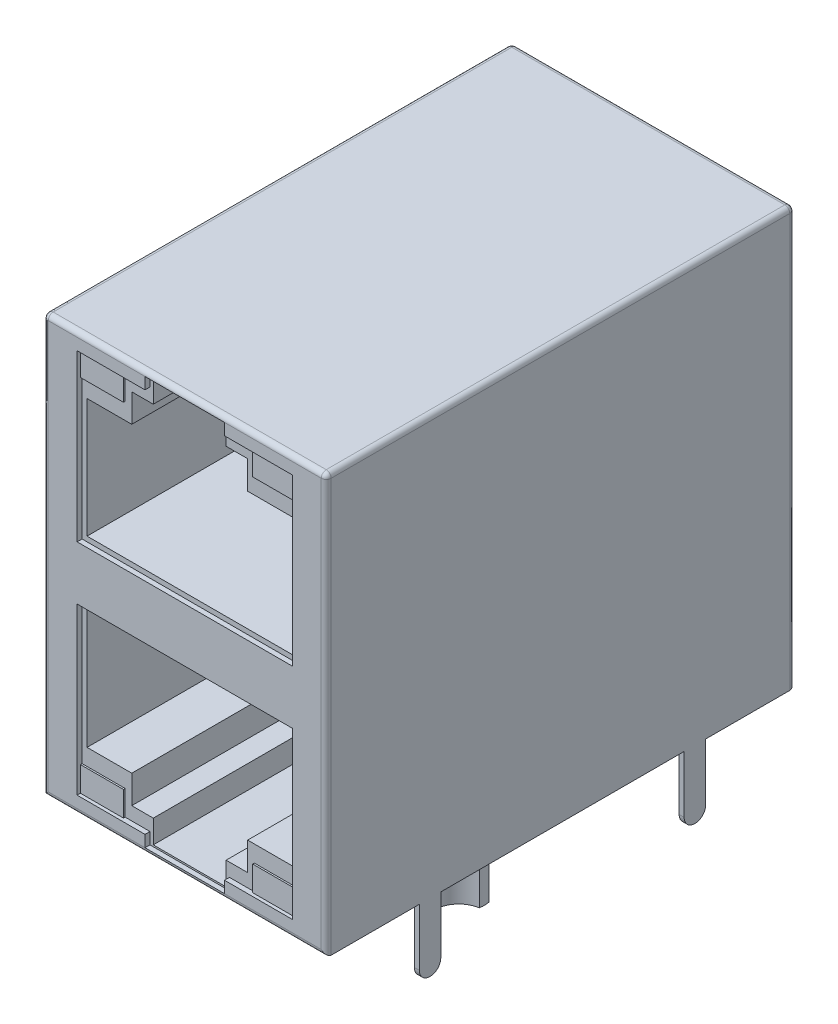
SolidWorks part; units mm, degrees
ref_plane "前视基准面" through (0, 0, 0) normal (0, 0, 1) x (1, 0, 0)
ref_plane "上视基准面" through (0, 0, 0) normal (0, 1, 0) x (1, 0, 0)
ref_plane "右视基准面" through (0, 0, 0) normal (1, 0, 0) x (0, 0, -1)
other "Configuration Table"
sketch "草图1" plane through (0, 0, 0) normal (0, 1, 0) x (1, 0, 0)
  line L0 (0, 0) -> (17.09, 0)
  line L1 (17.09, 0) -> (17.09, 28.3)
  line L2 (17.09, 28.3) -> (0, 28.3)
  line L3 (0, 28.3) -> (0, 0)
extrude "凸台-拉伸1" add sketch "草图1" along normal blind 25.25
sketch "草图2" plane through (17.09, 0, 0) normal (1, 0, 0) x (0, 0, -1)
  line L1 (0, 0) -> (28.3, 0) construction
  line L2 (21.62, 0) -> (21.62, -3.45)
  line L3 (22.92, 0) -> (21.62, 0)
  line L4 (6.92, -3.45) -> (6.92, 0)
  line L5 (6.92, 0) -> (5.62, 0)
  line L6 (5.62, 0) -> (5.62, -3.45)
  line L7 (22.92, -3.45) -> (22.92, 0)
  arc A0 (5.62, -3.45) -> (6.92, -3.45) centre (6.27, -3.45) ccw
  arc A1 (21.62, -3.45) -> (22.92, -3.45) centre (22.27, -3.45) ccw
extrude "凸台-拉伸2" add sketch "草图2" against normal blind 0.3
sketch "草图4" plane through (0, 0, 0) normal (-1, 0, 0) x (0, 0, 1)
  line L3 (-5.62, -3.45) -> (-5.62, 0) construction
  line L4 (-5.62, 0) -> (-6.92, 0) construction
  line L5 (-6.92, 0) -> (-6.92, -3.45) construction
  line L9 (-5.62, -3.45) -> (-5.62, 0)
  line L10 (-5.62, 0) -> (-6.92, 0)
  line L11 (-6.92, 0) -> (-6.92, -3.45)
  line L14 (-25.68, -3.45) -> (-25.68, 0)
  line L15 (-26.98, 0) -> (-26.98, -3.45)
  line L16 (-25.68, 0) -> (-26.98, 0)
  arc A1 (-6.92, -3.45) -> (-5.62, -3.45) centre (-6.27, -3.45) ccw construction
  arc A3 (-6.92, -3.45) -> (-5.62, -3.45) centre (-6.27, -3.45) ccw
  arc A4 (-26.98, -3.45) -> (-25.68, -3.45) centre (-26.33, -3.45) ccw
extrude "凸台-拉伸3" add sketch "草图4" against normal blind 0.3
sketch "草图5" plane through (0, 0, 0) normal (0, -1, 0) x (1, 0, 0)
  arc A0 (1.307, -10.5521) -> (1.307, -11.1279) centre (2.83, -10.84) ccw
  arc A2 (1.307, -10.5521) -> (2.5421, -9.317) centre (1.0622, -9.0722) ccw
  arc A3 (3.1179, -9.317) -> (4.353, -10.5521) centre (4.5978, -9.0722) ccw
  arc A4 (4.353, -11.1279) -> (3.1179, -12.363) centre (4.5978, -12.6078) ccw
  arc A5 (2.5421, -12.363) -> (1.307, -11.1279) centre (1.0622, -12.6078) ccw
  arc A6 (3.1179, -9.317) -> (2.5421, -9.317) centre (2.83, -10.84) ccw
  arc A7 (4.353, -11.1279) -> (4.353, -10.5521) centre (2.83, -10.84) ccw
  arc A8 (2.5421, -12.363) -> (3.1179, -12.363) centre (2.83, -10.84) ccw
  arc A9 (14.5479, -12.363) -> (13.9721, -12.363) centre (14.26, -10.84) cw
  arc A10 (12.737, -11.1279) -> (12.737, -10.5521) centre (14.26, -10.84) cw
  arc A11 (13.9721, -9.317) -> (14.5479, -9.317) centre (14.26, -10.84) cw
  arc A12 (14.5479, -12.363) -> (15.783, -11.1279) centre (16.0278, -12.6078) cw
  arc A13 (12.737, -11.1279) -> (13.9721, -12.363) centre (12.4922, -12.6078) cw
  arc A14 (13.9721, -9.317) -> (12.737, -10.5521) centre (12.4922, -9.0722) cw
  arc A15 (15.783, -10.5521) -> (14.5479, -9.317) centre (16.0278, -9.0722) cw
  arc A16 (15.783, -10.5521) -> (15.783, -11.1279) centre (14.26, -10.84) cw
  dimension "D1" = 4
extrude "凸台-拉伸4" add sketch "草图5" along normal blind 3.3
sketch "草图7" plane through (0, 0, 0) normal (0, -1, 0) x (1, 0, 0)
  circle A1 centre (5.5, -13.65) radius 0.25
  circle A2 centre (7.53, -13.65) radius 0.25
  circle A3 centre (5.5, -11.85) radius 0.25
  circle A4 centre (7.53, -11.85) radius 0.25
  circle A5 centre (9.56, -11.85) radius 0.25
  circle A6 centre (11.59, -11.85) radius 0.25
  circle A7 centre (9.56, -13.65) radius 0.25
  circle A8 centre (11.59, -13.65) radius 0.25
  circle A9 centre (5.245, -15.54) radius 0.25
  circle A10 centre (6.515, -16.81) radius 0.25
  circle A11 centre (5.245, -18.0779) radius 0.25
  circle A12 centre (6.515, -19.3479) radius 0.25
  circle A13 centre (5.245, -20.6158) radius 0.25
  circle A14 centre (6.515, -21.8858) radius 0.25
  circle A15 centre (6.515, -24.4237) radius 0.25
  circle A16 centre (5.245, -25.6916) radius 0.25
  circle A17 centre (5.245, -23.1537) radius 0.25
  circle A18 centre (6.515, -26.9616) radius 0.25
  circle A19 centre (10.575, -26.9616) radius 0.25
  circle A20 centre (11.845, -23.1537) radius 0.25
  circle A21 centre (11.845, -25.6916) radius 0.25
  circle A22 centre (10.575, -24.4237) radius 0.25
  circle A23 centre (10.575, -21.8858) radius 0.25
  circle A24 centre (11.845, -20.6158) radius 0.25
  circle A25 centre (10.575, -19.3479) radius 0.25
  circle A26 centre (11.845, -18.0779) radius 0.25
  circle A27 centre (10.575, -16.81) radius 0.25
  circle A28 centre (11.845, -15.54) radius 0.25
extrude "凸台-拉伸5" add sketch "草图7" along normal blind 3.15
fillet "圆角1" radius 0.3 9 edges at (0, 12.625, -28.3) (8.545, 25.25, -28.3) (17.09, 12.625, -28.3) (8.545, 0, 0) (17.09, 12.625, 0) (8.545, 25.25, 0) (0, 12.625, 0) (0, 25.25, -14.15) (17.09, 25.25, -14.15)
sketch "草图8" plane through (0, 0, 0) normal (0, 0, 1) x (1, 0, 0)
  line L2 (15.045, 14.25) -> (2.045, 14.25)
  line L3 (2.045, 14.25) -> (2.045, 24.25)
  line L5 (6.145, 24.95) -> (6.145, 24.25)
  line L6 (6.145, 24.25) -> (2.045, 24.25)
  line L7 (10.945, 24.25) -> (15.045, 24.25)
  line L8 (10.945, 24.95) -> (10.945, 24.25)
  line L9 (15.045, 14.25) -> (15.045, 24.25)
  line L10 (16.79, 24.95) -> (0.3, 24.95) construction
  line L11 (10.945, 24.95) -> (6.145, 24.95)
  line L14 (10.945, 0.3) -> (6.145, 0.3)
  line L15 (15.045, 11) -> (15.045, 1)
  line L16 (10.945, 0.3) -> (10.945, 1)
  line L17 (10.945, 1) -> (15.045, 1)
  line L18 (6.145, 1) -> (2.045, 1)
  line L19 (6.145, 0.3) -> (6.145, 1)
  line L20 (2.045, 11) -> (2.045, 1)
  line L21 (15.045, 11) -> (2.045, 11)
extrude "切除-拉伸1" cut sketch "草图8" against normal blind 10
sketch "草图9" plane through (0, 0, -10) normal (0, 0, 1) x (1, 0, 0)
  line L0 (2.045, 24.25) -> (2.045, 21.75)
  line L1 (2.045, 24.25) -> (2.045, 14.25) construction
  line L2 (2.045, 21.75) -> (5.045, 21.75)
  line L3 (5.045, 21.75) -> (5.045, 23.45)
  line L4 (5.045, 23.45) -> (6.345, 23.45)
  line L5 (6.345, 23.45) -> (6.345, 24.85)
  line L6 (6.345, 24.85) -> (10.745, 24.85)
  line L7 (2.045, 24.25) -> (6.145, 24.25)
  line L9 (10.745, 23.45) -> (10.745, 24.85)
  line L10 (12.045, 23.45) -> (10.745, 23.45)
  line L11 (12.045, 21.75) -> (12.045, 23.45)
  line L12 (15.045, 21.75) -> (12.045, 21.75)
  line L13 (6.145, 24.25) -> (6.145, 24.95)
  line L14 (6.145, 24.95) -> (10.945, 24.95)
  line L15 (10.945, 24.95) -> (10.945, 24.25)
  line L16 (10.945, 24.25) -> (15.045, 24.25)
  line L17 (15.045, 24.25) -> (15.045, 21.75)
  line L20 (15.045, 1) -> (15.045, 3.5)
  line L21 (10.945, 1) -> (15.045, 1)
  line L22 (10.945, 0.3) -> (10.945, 1)
  line L23 (6.145, 0.3) -> (10.945, 0.3)
  line L24 (6.145, 1) -> (6.145, 0.3)
  line L25 (15.045, 3.5) -> (12.045, 3.5)
  line L26 (12.045, 3.5) -> (12.045, 1.8)
  line L27 (12.045, 1.8) -> (10.745, 1.8)
  line L28 (10.745, 1.8) -> (10.745, 0.4)
  line L29 (2.045, 1) -> (6.145, 1)
  line L30 (6.345, 0.4) -> (10.745, 0.4)
  line L31 (6.345, 1.8) -> (6.345, 0.4)
  line L32 (5.045, 1.8) -> (6.345, 1.8)
  line L33 (5.045, 3.5) -> (5.045, 1.8)
  line L34 (2.045, 3.5) -> (5.045, 3.5)
  line L35 (2.045, 1) -> (2.045, 3.5)
extrude "凸台-拉伸6" add sketch "草图9" along normal blind 9.7
sketch "草图10" plane through (0, 0, -0.3) normal (0, 0, 1) x (1, 0, 0)
  line L0 (2.045, 24.25) -> (4.645, 24.25)
  line L1 (6.145, 24.25) -> (2.045, 24.25) construction
  line L2 (4.645, 24.25) -> (4.645, 22.75)
  line L3 (4.645, 22.75) -> (2.045, 22.75)
  line L4 (2.045, 24.25) -> (2.045, 21.75) construction
  line L5 (2.045, 22.75) -> (2.045, 24.25)
  line L8 (15.045, 22.75) -> (15.045, 24.25)
  line L9 (12.445, 22.75) -> (15.045, 22.75)
  line L10 (12.445, 24.25) -> (12.445, 22.75)
  line L11 (15.045, 24.25) -> (12.445, 24.25)
  line L13 (15.045, 1) -> (12.445, 1)
  line L14 (12.445, 1) -> (12.445, 2.5)
  line L15 (12.445, 2.5) -> (15.045, 2.5)
  line L16 (15.045, 2.5) -> (15.045, 1)
  line L17 (2.045, 2.5) -> (2.045, 1)
  line L18 (4.645, 2.5) -> (2.045, 2.5)
  line L19 (4.645, 1) -> (4.645, 2.5)
  line L20 (2.045, 1) -> (4.645, 1)
extrude "凸台-拉伸7" add sketch "草图10" along normal blind 0.1
sketch "草图11" plane through (0, 0, -10) normal (0, 0, 1) x (1, 0, 0)
  line L0 (15.045, 3.5) -> (15.045, 11) construction
  line L1 (15.045, 11) -> (2.045, 11) construction
  line L2 (2.045, 11) -> (2.045, 3.5) construction
  line L3 (15.045, 3.5) -> (15.045, 11)
  line L4 (15.045, 11) -> (2.045, 11)
  line L5 (2.045, 11) -> (2.045, 3.5)
  line L6 (14.745, 3.5) -> (14.745, 10.7)
  line L7 (14.745, 10.7) -> (2.345, 10.7)
  line L8 (2.345, 10.7) -> (2.345, 3.5)
  line L9 (2.345, 3.5) -> (2.045, 3.5)
  line L10 (14.745, 3.5) -> (15.045, 3.5)
  line L13 (14.745, 21.75) -> (15.045, 21.75)
  line L14 (2.345, 21.75) -> (2.045, 21.75)
  line L15 (2.345, 14.55) -> (2.345, 21.75)
  line L16 (14.745, 14.55) -> (2.345, 14.55)
  line L17 (14.745, 21.75) -> (14.745, 14.55)
  line L18 (2.045, 14.25) -> (2.045, 21.75)
  line L19 (15.045, 14.25) -> (2.045, 14.25)
  line L20 (15.045, 21.75) -> (15.045, 14.25)
  dimension "D1" = 0.3
extrude "凸台-拉伸8" add sketch "草图11" along normal up to surface (9.7 mm away) up to face at (8.545, 1.83, -0.3)
